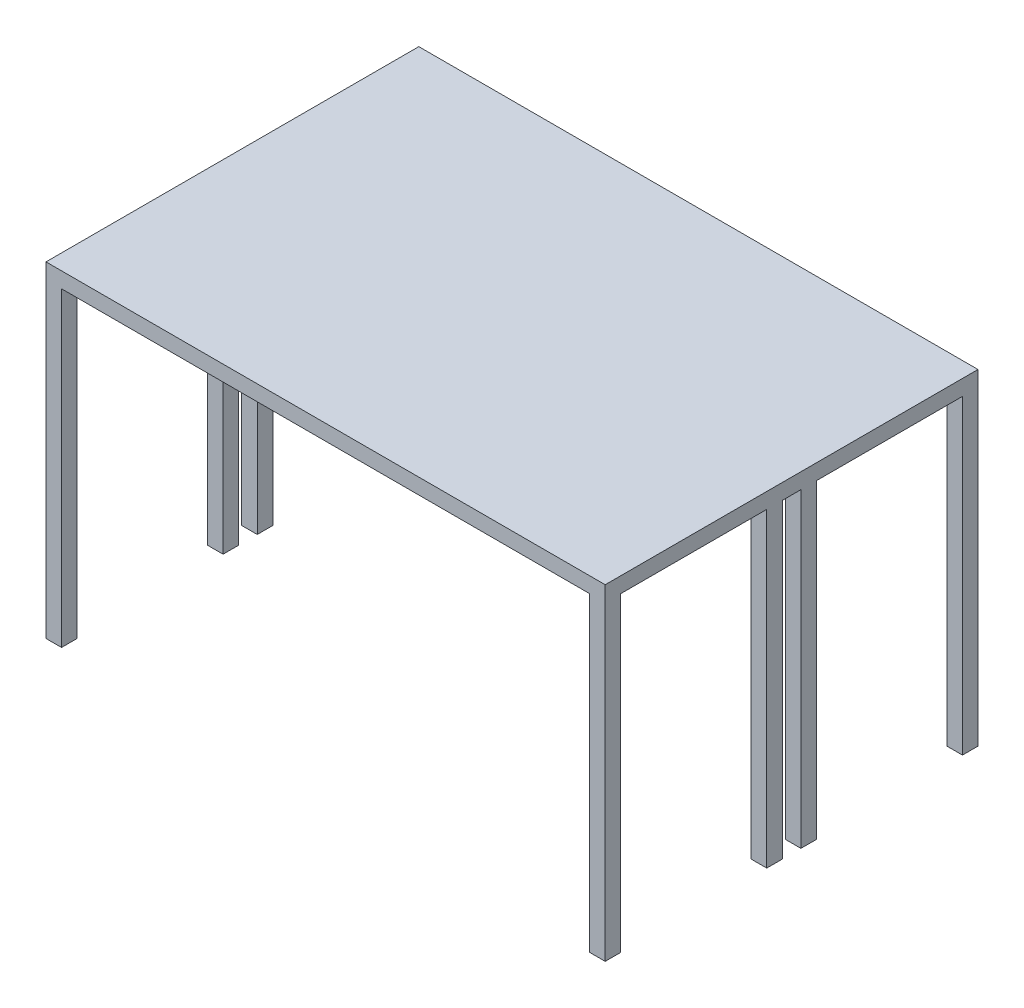
SolidWorks part; units mm, degrees
ref_plane "Front Plane" through (0, 0, 0) normal (0, 0, 1) x (1, 0, 0)
ref_plane "Top Plane" through (0, 0, 0) normal (0, 1, 0) x (1, 0, 0)
ref_plane "Right Plane" through (0, 0, 0) normal (1, 0, 0) x (0, 0, -1)
sketch "Sketch1" plane through (0, 0, 0) normal (0, 1, 0) x (1, 0, 0)
  line L1 (-900, 600) -> (900, 600)
  line L2 (-900, 600) -> (-900, -600)
  line L3 (-900, -600) -> (900, -600)
  line L4 (900, 600) -> (900, -600)
  line L5 (-900, 600) -> (900, -600) construction
  line L6 (-900, -600) -> (900, 600) construction
  point P0 (0, 0)
  dimension "D1" = 1800
  dimension "D2" = 1200
extrude "Boss-Extrude1" add sketch "Sketch1" along normal blind 50
sketch "Sketch2" plane through (0, 0, 0) normal (0, -1, 0) x (1, 0, 0)
  line L0 (900, 0) -> (-900, 0) construction
  line L1 (900, -600) -> (850, -600)
  line L2 (900, -600) -> (900, -550)
  line L3 (900, -550) -> (850, -550)
  line L4 (850, -600) -> (850, -550)
  line L5 (900, 600) -> (900, -600) construction
  line L6 (-900, -600) -> (-900, 600) construction
  line L7 (0, -600) -> (0, 600) construction
  line L8 (900, -600) -> (-900, -600) construction
  line L9 (-900, 600) -> (900, 600) construction
  line L10 (-900, -600) -> (-900, -550)
  line L11 (-900, -600) -> (-850, -600)
  line L12 (-850, -600) -> (-850, -550)
  line L13 (-900, -550) -> (-850, -550)
  line L14 (-900, 550) -> (-850, 550)
  line L15 (-900, 600) -> (-900, 550)
  line L16 (-900, 600) -> (-850, 600)
  line L17 (-850, 600) -> (-850, 550)
  line L18 (900, 600) -> (900, 550)
  line L19 (900, 600) -> (850, 600)
  line L20 (850, 600) -> (850, 550)
  line L21 (900, 550) -> (850, 550)
  line L22 (-850, 30) -> (-850, 80)
  line L23 (-900, -30) -> (-850, -30)
  line L24 (-900, -30) -> (-900, -80)
  line L25 (-900, -80) -> (-850, -80)
  line L26 (-850, -30) -> (-850, -80)
  line L27 (-900, 80) -> (-850, 80)
  line L28 (-900, 30) -> (-900, 80)
  line L29 (-900, 30) -> (-850, 30)
  line L30 (850, -30) -> (850, -80)
  line L31 (900, -80) -> (850, -80)
  line L32 (900, -30) -> (900, -80)
  line L33 (900, -30) -> (850, -30)
  line L34 (900, 30) -> (850, 30)
  line L35 (900, 30) -> (900, 80)
  line L36 (850, 30) -> (850, 80)
  line L37 (900, 80) -> (850, 80)
  dimension "D1" = 50
  dimension "D2" = 50
  dimension "D3" = 50
  dimension "D4" = 50
  dimension "D5" = 30
extrude "Boss-Extrude2" add sketch "Sketch2" along normal blind 1000
